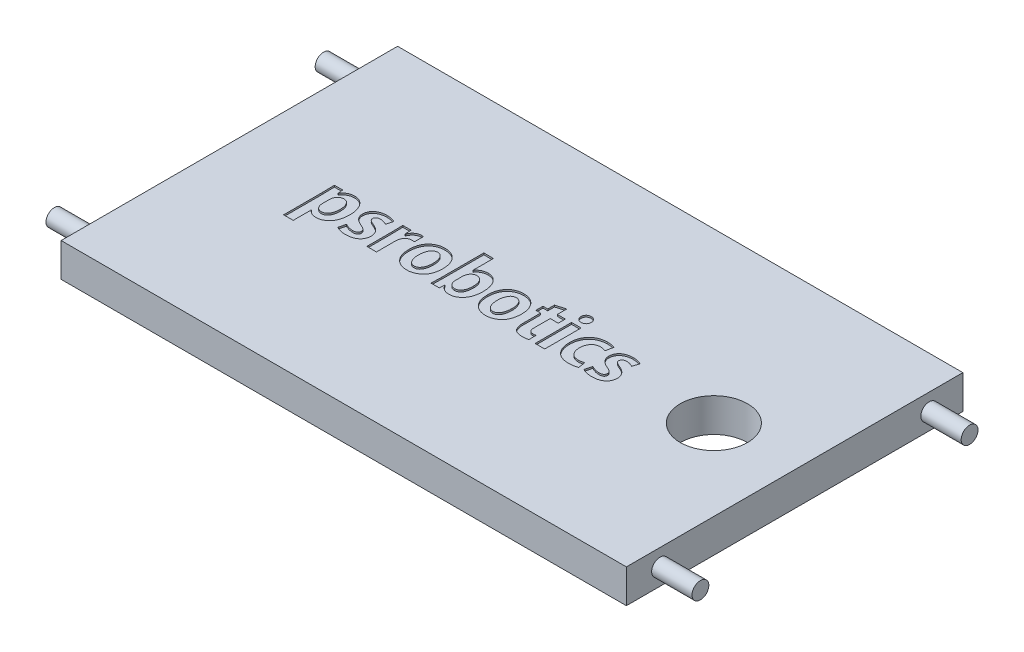
SolidWorks part; units mm, degrees
ref_plane "前视基准面" through (0, 0, 0) normal (0, 0, 1) x (1, 0, 0)
ref_plane "上视基准面" through (0, 0, 0) normal (0, 1, 0) x (1, 0, 0)
ref_plane "右视基准面" through (0, 0, 0) normal (1, 0, 0) x (0, 0, -1)
sketch "草图1" plane through (0, 0, 0) normal (0, 1, 0) x (1, 0, 0)
  line L1 (-84, -50) -> (84, -50)
  line L2 (-84, -50) -> (-84, 50)
  line L3 (-84, 50) -> (84, 50)
  line L4 (84, -50) -> (84, 50)
  line L5 (-84, -50) -> (84, 50) construction
  line L6 (-84, 50) -> (84, -50) construction
  point P0 (0, 0)
  dimension "D1" = 100
  dimension "D2" = 168
extrude "凸台-拉伸1" add sketch "草图1" along normal blind 10
sketch "草图2" plane through (-84, 0, 0) normal (-1, 0, 0) x (0, 0, 1)
  line L0 (-50, 10) -> (50, 0)
  line L1 (50, 10) -> (-50, 0)
  line L2 (0, 5) -> (40, 5)
  line L3 (0, 5) -> (-40, 5)
  line L4 (-50, 0) -> (50, 0)
  line L5 (50, 0) -> (50, 10)
  line L6 (50, 10) -> (-50, 10)
  line L7 (-50, 10) -> (-50, 0)
  line L8 (-50, 0) -> (50, 0)
  line L9 (50, 0) -> (50, 10)
  line L10 (50, 10) -> (-50, 10)
  line L11 (-50, 10) -> (-50, 0)
  circle A0 centre (-40, 5) radius 2.5
  circle A1 centre (40, 5) radius 2.5
  dimension "D4" = 5
  dimension "D5" = 5
  dimension "D2" = 40
  dimension "D3" = 40
  dimension "D1" = 0
extrude "凸台-拉伸2" add sketch "草图2" along normal blind 12 contours A0 | A1
sketch "草图3" plane through (84, 0, 0) normal (1, 0, 0) x (0, 0, -1)
  circle A0 centre (-40, 5) radius 2.5 construction
  circle A1 centre (40, 5) radius 2.5 construction
  circle A2 centre (-40, 5) radius 2.5
  circle A3 centre (40, 5) radius 2.5
extrude "凸台-拉伸3" add sketch "草图3" along normal blind 12
sketch "草图4" plane through (0, 10, 0) normal (0, 1, 0) x (1, 0, 0)
  line L0 (0, 0) -> (-60, 0)
  line L1 (0, 0) -> (60, 0)
  line L4 (84, -50) -> (84, 50)
  line L5 (84, 50) -> (-84, 50)
  line L6 (-84, 50) -> (-84, -50)
  line L7 (-84, -50) -> (84, -50)
  line L8 (84, -50) -> (84, 50)
  line L9 (84, 50) -> (-84, 50)
  line L10 (-84, 50) -> (-84, -50)
  line L11 (-84, -50) -> (84, -50)
  circle A0 centre (-60, 0) radius 10
  circle A1 centre (60, 0) radius 10
  dimension "D3" = 20
  dimension "D5" = 20
  dimension "D2" = 60
  dimension "D4" = 60
  dimension "D1" = 0
extrude "切除-拉伸1" cut sketch "草图4" against normal blind 10
sketch "草图6" plane through (0, 10, 0) normal (0, 1, 0) x (1, 0, 0)
  text T0 "psrobotics" font "@Adobe Gothic Std B" height in points 48
extrude "切除-拉伸2" cut sketch "草图6" against normal blind 0.5
